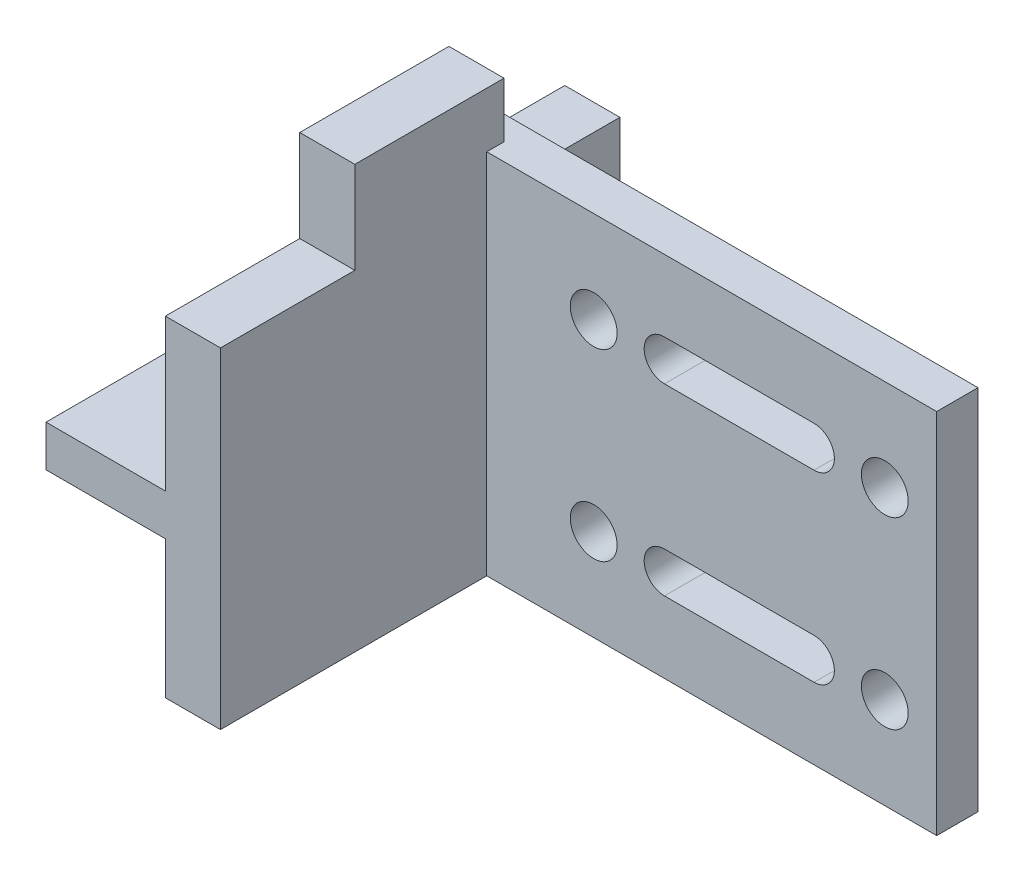
SolidWorks part; units mm, degrees
ref_plane "前视基准面" through (0, 0, 0) normal (0, 0, 1) x (1, 0, 0)
ref_plane "上视基准面" through (0, 0, 0) normal (0, 1, 0) x (1, 0, 0)
ref_plane "右视基准面" through (0, 0, 0) normal (1, 0, 0) x (0, 0, -1)
sketch "草图1" plane through (0, 0, 0) normal (0, 0, 1) x (1, 0, 0)
  line L8 (-66.2081, 0) -> (66.2081, 0) construction
  line L9 (-27.5, -10) -> (21.5, -10)
  line L11 (-27.5, 10) -> (21.5, 10)
  line L13 (-8.1447, 0) -> (8.1447, 0) construction
  line L14 (-8.1447, 2.212) -> (8.1447, 2.212)
  line L15 (-27.5, 10) -> (-33.5, 10)
  line L16 (-33.5, 10) -> (-33.5, -10)
  line L17 (-33.5, -10) -> (-27.5, -10)
  line L18 (21.5, 10) -> (21.5, -10)
  line L21 (-8.1447, -2.212) -> (8.1447, -2.212)
  circle A0 centre (-15.85, 0) radius 2.55
  circle A1 centre (15.85, 0) radius 2.55
  arc A2 (-8.1447, 2.212) -> (-8.1447, -2.212) centre (-8.1447, 0) ccw
  arc A3 (8.1447, -2.212) -> (8.1447, 2.212) centre (8.1447, 0) ccw
  point P0 (0, 0)
  point P5 (0, 0)
  point P11 (0, 0)
  dimension "D3" = 5.1
  dimension "D4" = 5.1
  dimension "D1" = 33.5
  dimension "D2" = 20
  dimension "D5" = 15.85
  dimension "D6" = 15.85
  dimension "D7" = 21.5
extrude "凸台-拉伸1" add sketch "草图1" along normal blind 4.5
sketch "草图2" plane through (0, 0, 4.5) normal (0, 0, 1) x (1, 0, 0)
  line L0 (-27.5, -10) -> (-27.5, 10)
  line L1 (-33.5, -10) -> (21.5, -10) construction
  line L2 (21.5, 10) -> (-33.5, 10) construction
  line L3 (-27.5, 10) -> (-33.5, 10)
  line L4 (-33.5, 10) -> (-33.5, -10) construction
  line L5 (-33.5, 10) -> (-33.5, -10)
  line L6 (-33.5, -10) -> (-27.5, -10)
  dimension "D1" = 6
extrude "凸台-拉伸2" add sketch "草图2" along normal blind 29
sketch "草图3" plane through (-33.5, 0, 0) normal (-1, 0, 0) x (0, 0, 1)
  line L0 (0, 10) -> (4.5, 10)
  line L1 (33.5, 10) -> (0, 10) construction
  line L2 (4.5, 10) -> (4.5, -10)
  line L3 (33.5, -10) -> (0, -10) construction
  line L4 (4.5, -10) -> (0, -10)
  line L5 (0, -10) -> (0, 10)
  dimension "D1" = 4.5
sketch "草图5" plane through (-33.5, 0, 0) normal (-1, 0, 0) x (0, 0, 1)
  line L0 (0, -5.5) -> (33.5, -5.5)
  line L1 (33.5, 10) -> (33.5, -10) construction
  line L2 (33.5, -5.5) -> (33.5, -10)
  line L3 (33.5, -10) -> (0, -10)
  line L4 (0, -10) -> (0, -5.5)
  line L5 (0, 5) -> (33.5, 5)
  line L6 (0, 10) -> (0, -10) construction
  line L7 (33.5, 5) -> (33.5, 9.5)
  line L8 (33.5, 9.5) -> (0, 9.5)
  line L9 (0, 9.5) -> (0, 5)
  dimension "D1" = 4.5
  dimension "D2" = 4.5
  dimension "D3" = 15
extrude "凸台-拉伸4" add sketch "草图5" along normal blind 13
sketch "草图6" plane through (0, -10, 0) normal (0, -1, 0) x (1, 0, 0)
  line L0 (-46.5, 0) -> (21.5, 0) construction
  line L1 (-33.5, 0) -> (-33.5, 33.5) construction
  line L2 (-33.5, 4.5) -> (-33.5, 0) construction
  line L3 (-46.5, 33.5) -> (-27.5, 33.5) construction
  circle A0 centre (-39.2, 1.6) radius 1.5
  circle A1 centre (-39.2, 10.6) radius 1.5
  dimension "D1" = 3
  dimension "D2" = 3
  dimension "D3" = 9
  dimension "D4" = 1.6
  dimension "D5" = 5.7
extrude "切除-拉伸1" cut sketch "草图6" against normal blind 13
sketch "草图8" plane through (0, 0, 0) normal (0, 0, -1) x (-1, 0, 0)
  line L0 (27.5, 10) -> (27.5, -10)
  line L1 (-21.5, 10) -> (33.5, 10) construction
  line L2 (46.5, -10) -> (-21.5, -10) construction
  line L3 (27.5, 10) -> (33.5, 10)
  line L4 (33.5, 10) -> (33.5, -10)
  line L5 (33.5, -10) -> (33.5, 10) construction
  line L6 (33.5, 10) -> (33.5, -10) construction
  line L7 (33.5, -10) -> (27.5, -10)
  dimension "D1" = 6
extrude "凸台-拉伸5" add sketch "草图8" along normal blind 10
sketch "草图9" plane through (-33.5, 0, 0) normal (-1, 0, 0) x (0, 0, 1)
  line L0 (0, -5.5) -> (-10, -5.5)
  line L1 (-10, -10) -> (-10, 10) construction
  line L3 (-10, -10) -> (0, -10)
  line L4 (0, -10) -> (0, -5.5)
  line L5 (-10, -5.5) -> (-15, -5.5)
  line L6 (-15, -5.5) -> (-15, -10)
  line L7 (-15, -10) -> (-10, -10)
  dimension "D1" = 5
sketch "草图11" plane through (0, 10, 0) normal (0, 1, 0) x (1, 0, 0)
  line L0 (-33.5, 10) -> (-27.5, 10)
  line L1 (-27.5, 10) -> (-27.5, -33.5)
  line L2 (-27.5, -33.5) -> (-33.5, -33.5)
  line L3 (-33.5, -33.5) -> (-33.5, 10)
extrude "凸台-拉伸7" add sketch "草图11" along normal blind 30
sketch "草图12" plane through (0, 0, 4.5) normal (0, 0, 1) x (1, 0, 0)
  line L0 (-10.0567, -10) -> (-10.0567, -4)
  line L1 (-27.5, -10) -> (21.5, -10) construction
  line L2 (-13.0567, -4) -> (-13.0567, -10)
  line L3 (-13.0567, -10) -> (-10.0567, -10)
  line L4 (-1000, 0) -> (49000, 0) construction
  line L5 (-13.0567, -4) -> (-10.0567, -4)
  line L6 (-10.0567, 10) -> (-10.0567, 4)
  line L7 (-13.0567, 10) -> (-10.0567, 10)
  line L8 (-13.0567, 4) -> (-13.0567, 10)
  line L9 (-13.0567, 4) -> (-10.0567, 4)
  line L10 (13.4433, -10) -> (13.4433, -4)
  line L11 (13.4433, -4) -> (10.4433, -4)
  line L12 (10.4433, -4) -> (10.4433, -10)
  line L13 (10.4433, -10) -> (13.4433, -10)
  line L14 (13.4433, 4) -> (10.4433, 4)
  line L15 (13.4433, 10) -> (13.4433, 4)
  line L16 (10.4433, 10) -> (13.4433, 10)
  line L17 (10.4433, 4) -> (10.4433, 10)
  arc A0 (-8.1447, 2.212) -> (-8.1447, -2.212) centre (-8.1447, 0) ccw construction
  point P9 (-10.3567, 0)
  dimension "D1" = 6
  dimension "D2" = 3
  dimension "D3" = 0.3
  dimension "D4" = 20.5
  dimension "D5" = 3
sketch "草图14" plane through (0, -10, 0) normal (0, -1, 0) x (1, 0, 0)
  line L0 (-13.0208, 4.5) -> (-13.0208, 0)
  line L1 (-27.5, 4.5) -> (21.5, 4.5) construction
  line L2 (-27.5, 0) -> (21.5, 0) construction
  line L3 (-13.0208, 4.5) -> (-10.0567, 4.5)
  line L4 (-10.0567, 4.5) -> (-10.0567, 0)
  line L5 (-10.0567, 0) -> (-13.0208, 0)
  line L6 (10.4433, 4.5) -> (10.4433, 0)
  line L7 (10.4433, 4.5) -> (13.4433, 4.5) construction
  line L8 (10.4433, 0) -> (13.4433, 0)
  line L9 (13.4433, 0) -> (13.4433, 4.5)
  line L10 (13.4433, 4.5) -> (10.4433, 4.5)
sketch "草图17" plane through (0, 40, 0) normal (0, 1, 0) x (1, 0, 0)
  line L4 (-33.5, 10) -> (-33.5, -33.5)
  line L5 (-33.5, -33.5) -> (-27.5, -33.5)
  line L6 (-27.5, -33.5) -> (-27.5, 10)
  line L7 (-27.5, 10) -> (-33.5, 10)
  line L8 (-33.5, 10) -> (-33.5, -33.5)
  line L9 (-33.5, -33.5) -> (-27.5, -33.5)
  line L10 (-27.5, -33.5) -> (-27.5, 10)
  line L11 (-27.5, 10) -> (-33.5, 10)
  dimension "D1" = 0
extrude "切除-拉伸3" cut sketch "草图17" against normal blind 14
sketch "草图18" plane through (0, 26, 0) normal (0, 1, 0) x (1, 0, 0)
  line L0 (-33.5, -33.5) -> (-33.5, 0) construction
  line L1 (-33.5, -2.6182) -> (-27.5, -2.6182)
  line L2 (-33.5, -2.6182) -> (-33.5, -18.8662)
  line L3 (-33.5, -18.8662) -> (-27.5, -18.8662)
  line L4 (-27.5, -2.6182) -> (-27.5, -18.8662)
  line L5 (-27.5, -33.5) -> (-27.5, 10) construction
extrude "凸台-拉伸12" add sketch "草图18" along normal blind 10
ref_plane "基准面1" through (0, 10, 0) normal (0, 1, 0) x (1, 0, 0)
mirror "镜向1" about plane through (0, 10, 0) normal (0, 1, 0) of "凸台-拉伸1"
sketch "草图20" plane through (-33.5, 0, 0) normal (-1, 0, 0) x (0, 0, 1)
  line L0 (0, 5) -> (-15, 5)
  line L1 (-15, 5) -> (-15, 9.5)
  line L2 (-15, 9.5) -> (0, 9.5)
  line L3 (0, 9.5) -> (0, 5)
  dimension "D1" = 4.5
  dimension "D2" = 15
extrude "凸台-拉伸13" add sketch "草图20" along normal blind 15
sketch "草图22" plane through (0, 5, 0) normal (0, -1, 0) x (1, 0, 0)
  circle A0 centre (-39.2, 10.6) radius 1.5
  circle A1 centre (-39.2, 1.6) radius 1.5
extrude "切除-拉伸5" cut sketch "草图22" against normal blind 15
sketch "草图23" plane through (0, -10, 0) normal (0, -1, 0) x (1, 0, 0)
  line L0 (-33.5, 0) -> (-46.5, 0)
  line L1 (-46.5, 0) -> (-46.5, 33.5)
  line L2 (-46.5, 33.5) -> (-33.5, 33.5)
  line L3 (-33.5, 33.5) -> (-33.5, 0)
extrude "切除-拉伸6" cut sketch "草图23" against normal blind 15
sketch "草图24" plane through (0, 5, 0) normal (0, -1, 0) x (1, 0, 0)
  circle A0 centre (-39.1984, -7.4) radius 1.5
  circle A1 centre (-39.2, 1.6) radius 1.5 construction
  dimension "D1" = 3
  dimension "D2" = 9
extrude "切除-拉伸7" cut sketch "草图24" against normal blind 15
